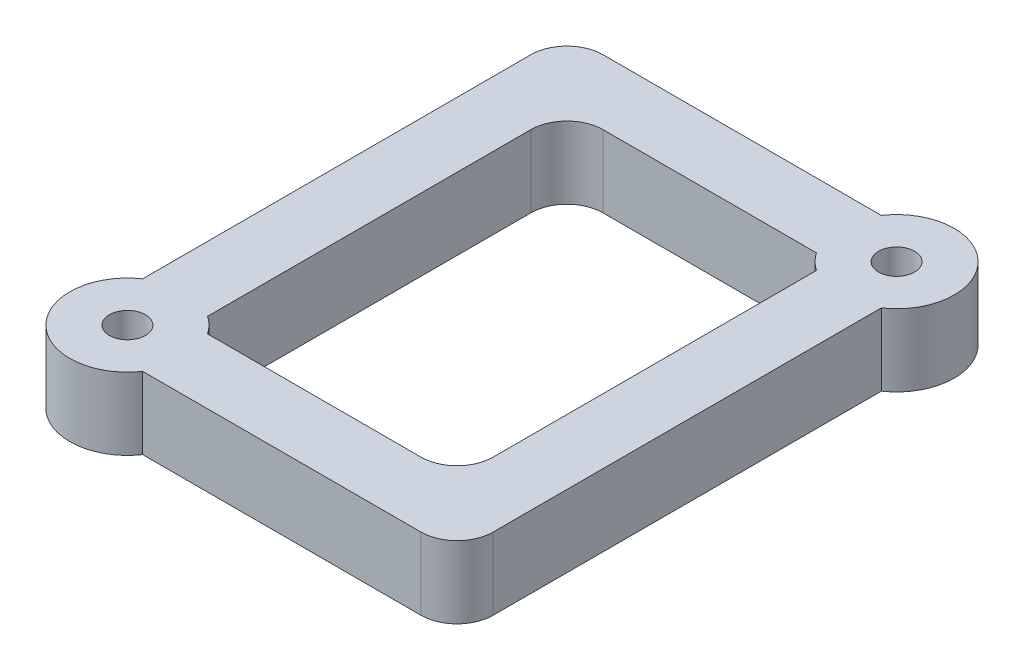
SolidWorks part; units mm, degrees
material "ABS"
ref_plane "Alzado" through (0, 0, 0) normal (0, 0, 1) x (1, 0, 0)
ref_plane "Planta" through (0, 0, 0) normal (0, 1, 0) x (1, 0, 0)
ref_plane "Vista lateral" through (0, 0, 0) normal (1, 0, 0) x (0, 0, -1)
sketch "Croquis1" plane through (0, 0, 0) normal (0, 1, 0) x (1, 0, 0)
  line L0 (-13.68, -11.9328) -> (-13.68, 17.49)
  line L1 (11.43, -15.24) -> (-11.43, -15.24) construction
  line L2 (11.43, -15.24) -> (11.43, 15.24) construction
  line L3 (11.43, 15.24) -> (-11.43, 15.24) construction
  line L4 (-11.43, -15.24) -> (-11.43, 15.24) construction
  line L5 (11.43, -15.24) -> (-11.43, 15.24) construction
  line L6 (11.43, 15.24) -> (-11.43, -15.24) construction
  line L7 (-13.68, 17.49) -> (8.1228, 17.49)
  line L8 (-9.18, -11.9328) -> (-9.18, 12.99)
  line L9 (-9.18, 12.99) -> (8.1228, 12.99)
  line L10 (-8.1228, -12.99) -> (9.18, -12.99)
  line L11 (9.18, -12.99) -> (9.18, 11.9328)
  line L12 (13.68, 11.9328) -> (13.68, -17.49)
  line L13 (13.68, -17.49) -> (-8.1228, -17.49)
  circle A0 centre (-11.43, -15.24) radius 1.25
  circle A1 centre (11.43, 15.24) radius 1.25
  circle A2 centre (-11.43, -15.24) radius 4
  circle A3 centre (11.43, 15.24) radius 4
  point P0 (0, 0)
  dimension "D1" = 2.5
  dimension "D4" = 8
  dimension "D2" = 30.48
  dimension "D3" = 22.86
  dimension "D5" = 4.5
  dimension "D6" = 4.5
  dimension "D7" = 4.5
  dimension "D8" = 4.5
extrude "Saliente-Extruir1" add sketch "Croquis1" along normal mid plane 5 contours A3 L7 L0 A2 L8 L9 | A3 L11 L10 A2 L13 L12 | A3 A1 | A2 A0
fillet "Redondeo1" radius 2.5 4 edges at (-13.68, 0, -17.49) (13.68, 0, 17.49) (9.18, 0, 12.99) (-9.18, 0, -12.99)
